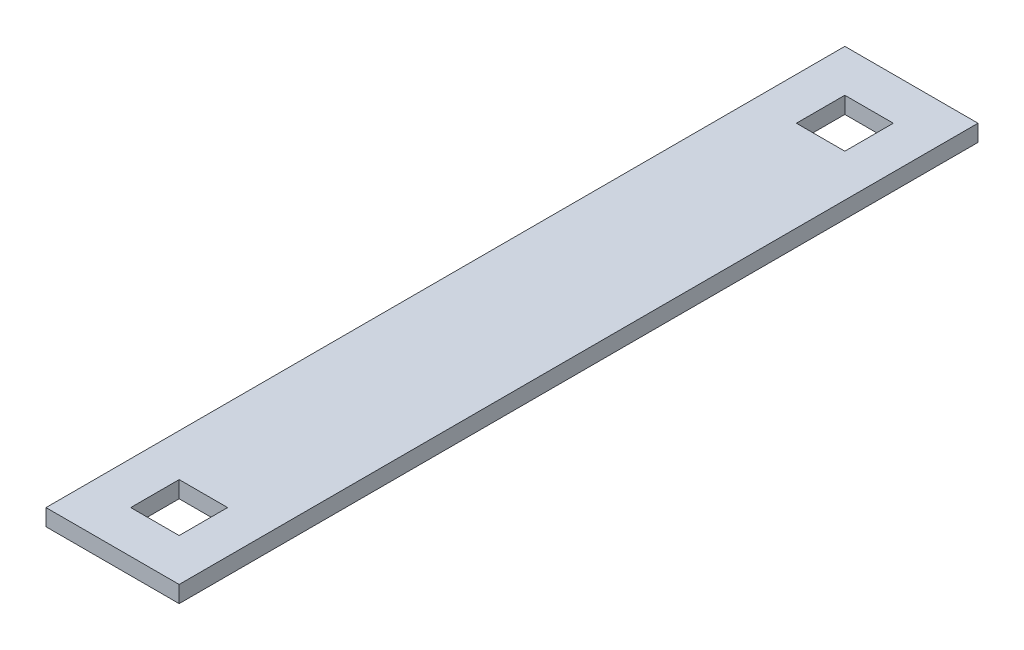
SolidWorks part; units mm, degrees
ref_plane "Front Plane" through (0, 0, 0) normal (0, 0, 1) x (1, 0, 0)
ref_plane "Top Plane" through (0, 0, 0) normal (0, 1, 0) x (1, 0, 0)
ref_plane "Right Plane" through (0, 0, 0) normal (1, 0, 0) x (0, 0, -1)
sketch "Sketch1" plane through (0, 0, 0) normal (0, 1, 0) x (1, 0, 0)
  line L1 (0, 101.5375) -> (12.7, 101.5375)
  line L2 (0, 101.5375) -> (0, 25.3375)
  line L3 (0, 25.3375) -> (12.7, 25.3375)
  line L4 (12.7, 101.5375) -> (12.7, 25.3375)
  line L5 (4.0372, 97.4975) -> (8.66, 97.4975)
  line L6 (4.0372, 97.4975) -> (4.0372, 92.8747)
  line L7 (4.0372, 92.8747) -> (8.66, 92.8747)
  line L8 (8.66, 97.4975) -> (8.66, 92.8747)
  line L48 (4.04, 34.0003) -> (8.66, 34.0003)
  line L65 (4.04, 34.0003) -> (4.04, 29.3775)
  line L66 (4.04, 29.3775) -> (8.66, 29.3775)
  line L67 (8.66, 34.0003) -> (8.66, 29.3775)
  point P8 (6.35, 101.5375)
  dimension "D1" = 12.7
  dimension "D2" = 76.2
  dimension "D3" = 4.6228
  dimension "D4" = 4.6228
  dimension "D5" = 4.04
  dimension "D6" = 4.04
  dimension "D8" = 4.04
  dimension "D9" = 4.04
  dimension "D10" = 4.62
  dimension "D11" = 4.6228
extrude "Boss-Extrude1" add sketch "Sketch1" along normal blind 1.5875
